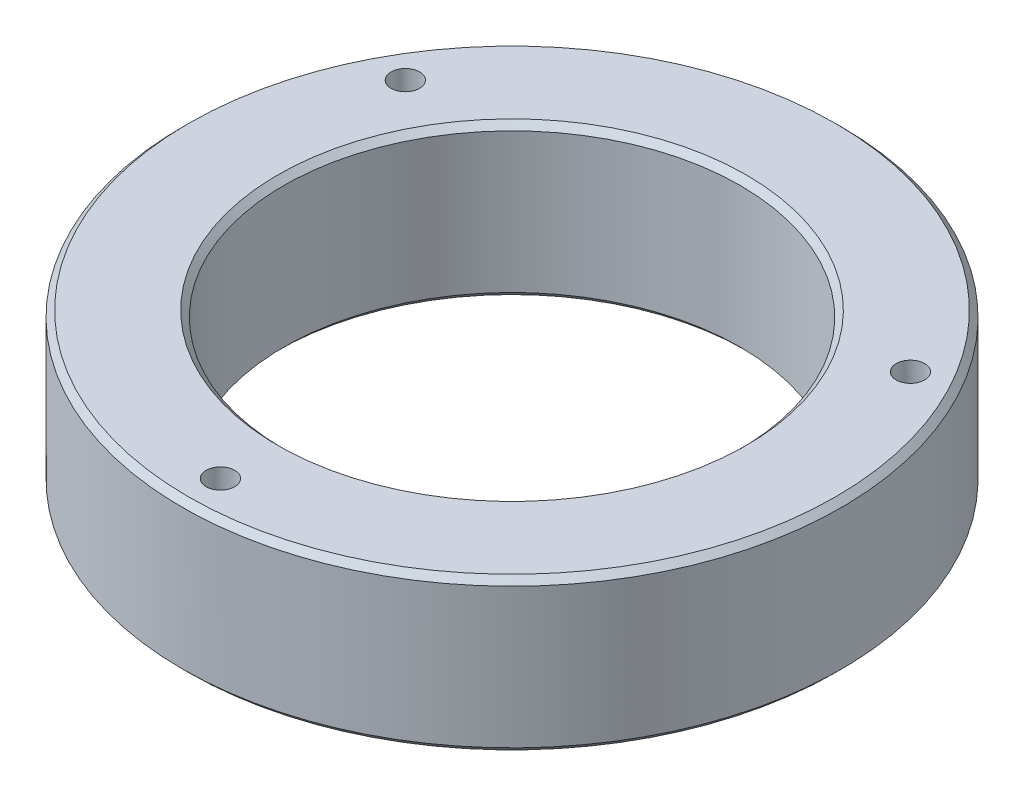
SolidWorks part; units mm, degrees
ref_plane "Front Plane" through (0, 0, 0) normal (1, 0, 0) x (0, 1, 0)
ref_plane "Top Plane" through (0, 0, 0) normal (0, 0, 1) x (0, 1, 0)
ref_plane "Right Plane" through (0, 0, 0) normal (0, 1, 0) x (-1, 0, 0)
sketch "Sketch1" plane through (0, 0, 0) normal (0, 0, 1) x (0, 1, 0)
  line L0 (-19.05, 82.5246) -> (19.05, 82.5246)
  line L1 (19.05, 82.5246) -> (19.05, 57.15)
  line L2 (19.05, 57.15) -> (-19.05, 57.15)
  line L3 (-19.05, 57.15) -> (-19.05, 82.5246)
  line L4 (-44.45, 0) -> (44.45, 0) construction
revolve "Revolve1" add sketch "Sketch1" angle 360 about L4
chamfer "Chamfer1" distance 1.524 angle 45 4 edges at (0, 19.05, -57.15) (0, -19.05, -57.15) (0, 19.05, -82.5246) (0, -19.05, -82.5246)
sketch "Sketch2" plane through (0, 0, 0) normal (0, 1, 0) x (-1, 0, 0)
  circle A0 centre (0, 73.025) radius 3.5687
  circle A1 centre (-63.246, -36.5252) radius 3.5687
  circle A2 centre (63.246, -36.5252) radius 3.5687
extrude "Cut-Extrude2" cut sketch "Sketch2" along normal blind 76.2 from offset 19.05
sketch "Sketch3" plane through (0, 0, 0) normal (0, 1, 0) x (-1, 0, 0)
  circle A0 centre (0, 73.025) radius 5.5626
  circle A1 centre (-63.246, -36.5252) radius 5.5626
  circle A2 centre (63.246, -36.5252) radius 5.5626
extrude "Cut-Extrude4" cut sketch "Sketch3" along normal blind 9.652 from offset 19.05
sketch "Sketch4" plane through (0, 0, 0) normal (0, 1, 0) x (-1, 0, 0)
  circle A0 centre (-69.85, 0) radius 3.9687
  circle A1 centre (69.85, 0) radius 3.9687
extrude "Cut-Extrude6" cut sketch "Sketch4" along normal blind 25.4 from offset 19.05
